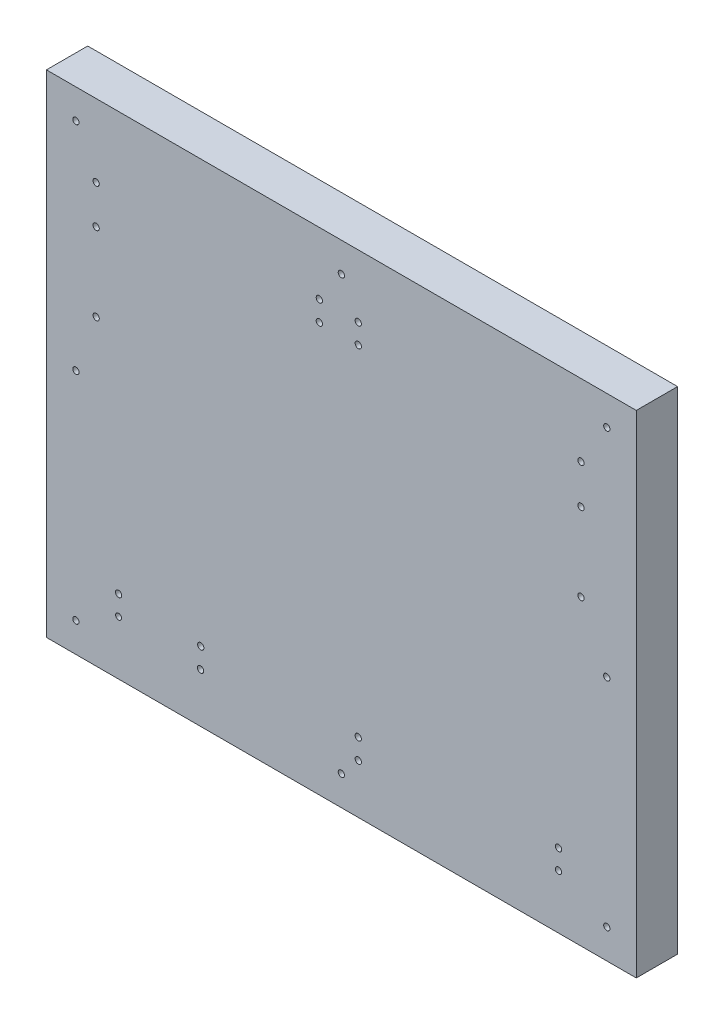
SolidWorks part; units mm, degrees
material "Buche"
ref_plane "Ebene vorne" through (0, 0, 0) normal (0, 0, 1) x (1, 0, 0)
ref_plane "Ebene oben" through (0, 0, 0) normal (0, 1, 0) x (1, 0, 0)
ref_plane "Ebene rechts" through (0, 0, 0) normal (1, 0, 0) x (0, 0, -1)
sketch "Skizze1" plane through (0, 0, 0) normal (0, 0, 1) x (1, 0, 0)
  line L1 (0, 0) -> (300, 0)
  line L2 (0, 0) -> (0, 250)
  line L3 (0, 250) -> (300, 250)
  line L4 (300, 0) -> (300, 250)
  circle A0 centre (15, 15) radius 1.6
  circle A1 centre (285, 15) radius 1.6
  circle A2 centre (285, 235) radius 1.6
  circle A3 centre (15, 235) radius 1.6
  circle A4 centre (150, 15) radius 1.6
  circle A5 centre (285, 125) radius 1.6
  circle A6 centre (15, 125) radius 1.6
  circle A7 centre (150, 235) radius 1.6
sketch "Skizze2" plane through (0, 0, 0) normal (0, 0, 1) x (1, 0, 0)
  circle A0 centre (158.6032, 25.1183) radius 1.6
  circle A1 centre (158.6032, 35.3655) radius 1.6
  circle A2 centre (260.4456, 27.5136) radius 1.6
  circle A3 centre (260.4456, 37.5125) radius 1.6
  circle A4 centre (271.8728, 153.8143) radius 1.6
  circle A5 centre (271.8729, 193.5089) radius 1.6
  circle A6 centre (271.8729, 213.3561) radius 1.6
  circle A7 centre (158.6035, 218.1341) radius 1.6
  circle A8 centre (138.7983, 208.1673) radius 1.6
  circle A9 centre (158.6032, 208.112) radius 1.6
  circle A10 centre (138.7983, 218.3576) radius 1.6
  circle A11 centre (25.2857, 193.5088) radius 1.6
  circle A12 centre (25.2857, 213.0654) radius 1.6
  circle A13 centre (25.2857, 153.8143) radius 1.6
  circle A14 centre (78.4044, 25.1183) radius 1.6
  circle A15 centre (36.7129, 27.5136) radius 1.5
  circle A16 centre (36.7129, 37.5602) radius 1.6
  circle A17 centre (78.5125, 35.3655) radius 1.6
  point P19 (22.0964, 8.9877)
sketch "Skizze4" plane through (0, 0, 0) normal (0, 0, 1) x (1, 0, 0)
  line L0 (270.8705, 12.4778) -> (241.8012, 12.4778)
  line L1 (241.8012, 12.4778) -> (241.8012, 20.4969)
  line L2 (241.8012, 20.4969) -> (255.8347, 20.4969)
  line L3 (255.8347, 20.4969) -> (255.8347, 42.5494)
  line L4 (255.8347, 42.5494) -> (270.8705, 42.5494)
  line L5 (270.8705, 42.5494) -> (270.8705, 12.4778)
  line L6 (55.3573, 12.4778) -> (26.2881, 12.4778)
  line L7 (26.2881, 42.5494) -> (41.3239, 42.5494)
  line L8 (41.3239, 42.5494) -> (41.3239, 20.4969)
  line L9 (41.3239, 20.4969) -> (55.3573, 20.4969)
  line L10 (55.3573, 20.4969) -> (55.3573, 12.4778)
  line L11 (171.2332, 20.9981) -> (146.0733, 20.9981)
  line L12 (146.0733, 20.9981) -> (146.0733, 41.0459)
  line L13 (146.0733, 41.0459) -> (91.0423, 41.0459)
  line L14 (91.0423, 41.0459) -> (91.0423, 20.9981)
  line L15 (91.0423, 20.9981) -> (70.9946, 20.9981)
  line L16 (70.9946, 20.9981) -> (70.9946, 49.065)
  line L17 (70.9946, 49.065) -> (171.2332, 49.065)
  line L18 (171.2332, 194.411) -> (125.9254, 194.411)
  line L19 (125.9254, 194.411) -> (125.9254, 222.4778)
  line L20 (125.9254, 222.4778) -> (171.2332, 222.4778)
  line L21 (171.2332, 222.4778) -> (171.2332, 194.411)
  line L22 (171.2332, 49.065) -> (171.2332, 20.9981)
  line L23 (276.8848, 141.7857) -> (238.7941, 141.7857)
  line L24 (238.7941, 141.7857) -> (238.7941, 146.7977)
  line L25 (238.7941, 146.7977) -> (262.8514, 146.7977)
  line L26 (262.8514, 146.7977) -> (262.8514, 221.9767)
  line L27 (262.8514, 221.9767) -> (238.7941, 221.9767)
  line L28 (238.7941, 221.9767) -> (238.7941, 232.0005)
  line L29 (238.7941, 232.0005) -> (276.8848, 232.0005)
  line L30 (276.8848, 232.0005) -> (276.8848, 141.7857)
  line L31 (58.3645, 141.7857) -> (20.2738, 141.7857)
  line L32 (20.2738, 141.7857) -> (20.2738, 232.0005)
  line L33 (20.2738, 232.0005) -> (58.3645, 232.0005)
  line L34 (58.3645, 232.0005) -> (58.3645, 221.9767)
  line L35 (58.3645, 221.9767) -> (34.3072, 221.9767)
  line L36 (34.3072, 221.9767) -> (34.3072, 146.7977)
  line L37 (34.3072, 146.7977) -> (58.3645, 146.7977)
  line L38 (58.3645, 146.7977) -> (58.3645, 141.7857)
  line L39 (26.2881, 42.5494) -> (26.2881, 12.4778)
extrude "Aufsatz-Linear austragen5" add sketch "Skizze1" along normal blind 21
extrude "Schnitt-Linear austragen2" cut sketch "Skizze2" along normal blind 21
extrude "Schnitt-Linear austragen4" cut sketch "Skizze4" along normal blind 1
